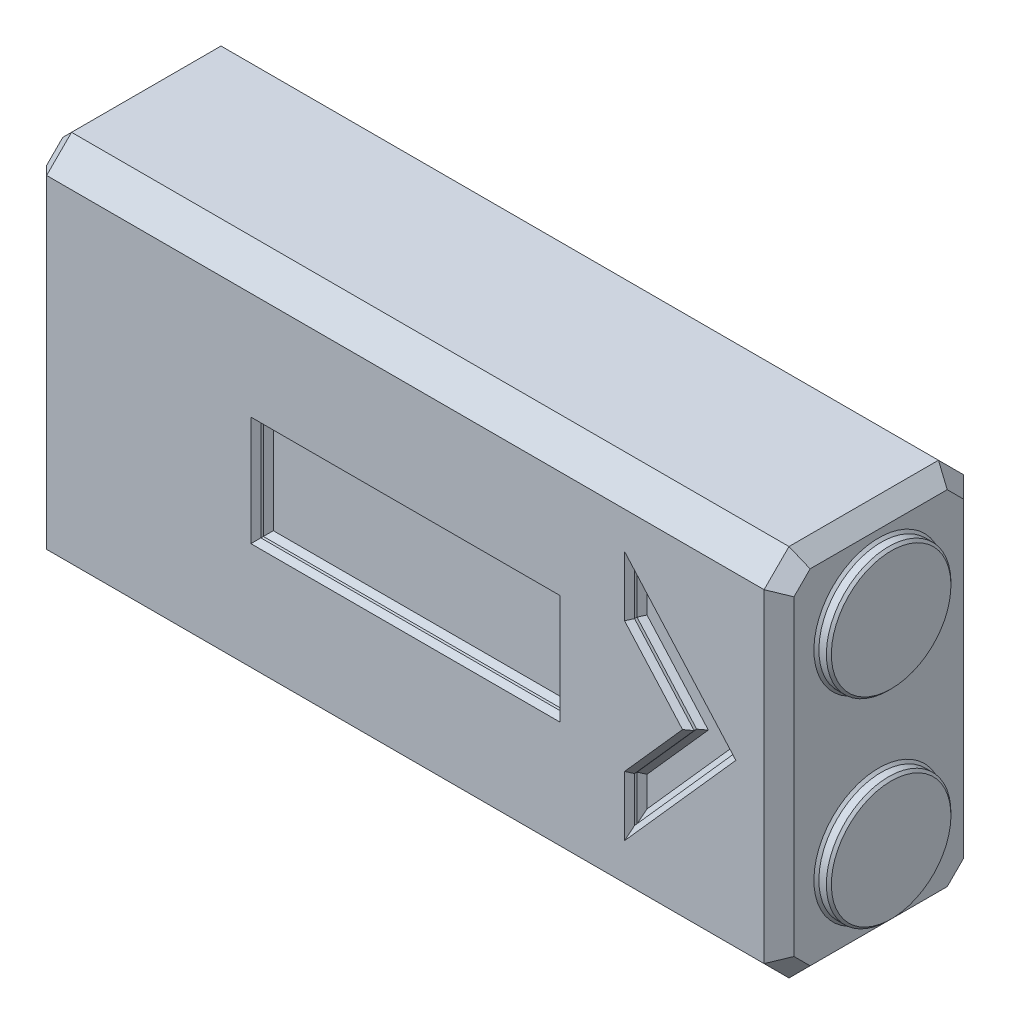
SolidWorks part; units mm, degrees
ref_plane "Front Plane" through (0, 0, 0) normal (0, 0, 1) x (1, 0, 0)
ref_plane "Top Plane" through (0, 0, 0) normal (0, 1, 0) x (1, 0, 0)
ref_plane "Right Plane" through (0, 0, 0) normal (1, 0, 0) x (0, 0, -1)
sketch "Sketch1" plane through (0, 0, 0) normal (0, 1, 0) x (1, 0, 0)
  line L0 (-75, 150) -> (75, -150) construction
  line L1 (-75, 150) -> (75, 150)
  line L2 (-75, 150) -> (-75, -150)
  line L3 (-75, -150) -> (75, -150)
  line L4 (75, 150) -> (75, -150)
  dimension "D1" = 150
  dimension "D2" = 300
extrude "Boss-Extrude1" add sketch "Sketch1" along normal mid plane 80
sketch "Sketch2" plane through (0, 0, 150) normal (0, 0, 1) x (1, 0, 0)
  line L0 (0, 51.0302) -> (0, -58.9796) construction
  line L1 (-40, 0) -> (40, 0) construction
  line L2 (-40, 35) -> (-100, 35) construction
  line L3 (-100, 35) -> (-100, -35) construction
  line L4 (-100, -35) -> (-40, -35) construction
  circle A0 centre (-40, 0) radius 25
  circle A1 centre (40, 0) radius 25
  arc A2 (-40, -35) -> (-40, 35) centre (-40, 0) ccw construction
  dimension "D1" = 50
  dimension "D2" = 70
  dimension "D3" = 80
  dimension "D4" = 60
extrude "Boss-Extrude2" add sketch "Sketch2" along normal blind 5
sketch "Sketch3" plane through (0, 40, 0) normal (0, 1, 0) x (1, 0, 0)
  line L0 (-20, 60) -> (20, -60) construction
  line L1 (-20, 60) -> (20, 60)
  line L2 (-20, 60) -> (-20, -60)
  line L3 (-20, -60) -> (20, -60)
  line L4 (20, 60) -> (20, -60)
  dimension "D1" = 40
  dimension "D2" = 120
extrude "Cut-Extrude1" cut sketch "Sketch3" against normal blind 5
sketch "Sketch4" plane through (0, 40, 0) normal (0, 1, 0) x (1, 0, 0)
  line L0 (0, -130) -> (-45, -90)
  line L1 (-45, -90) -> (-26.9376, -90)
  line L2 (-26.9376, -90) -> (0, -113.9445)
  line L3 (0, 0) -> (0, -130) construction
  line L4 (26.9376, -90) -> (0, -113.9445)
  line L5 (45, -90) -> (26.9376, -90)
  line L6 (0, -130) -> (45, -90)
  line L7 (-75, -150) -> (75, -150) construction
  dimension "D1" = 12
  dimension "D2" = 40
  dimension "D3" = 90
  dimension "D4" = 20
extrude "Cut-Extrude2" cut sketch "Sketch4" against normal blind 5
chamfer "Chamfer2" distance 10 angle 45 4 edges at (75, -40, 0) (-75, -40, 0) (75, 40, 0) (-75, 40, 0)
chamfer "Chamfer3" distance 2 angle 45 20 edges at (0, 35, -60) (20, 35, 0) (0, 35, 60) (-20, 35, 0) (0, 40, 60) (20, 40, 0) (-20, 40, 0) (0, 40, -60) (-22.5, 35, 110) (-35.9688, 35, 90) (-13.4688, 35, 101.9723) (13.4688, 35, 101.9723) (35.9688, 35, 90) (22.5, 35, 110) (-22.5, 40, 110) (-35.9688, 40, 90) (-13.4688, 40, 101.9723) (13.4688, 40, 101.9723) (35.9688, 40, 90) (22.5, 40, 110)
mirror "Mirror1" about plane through (0, 0, 0) normal (0, 0, 1) of "Boss-Extrude2"
chamfer "Chamfer4" distance 1 angle 45 4 edges at (15, 0, -155) (-15, 0, -155) (15, 0, 155) (-15, 0, 155)
chamfer "Chamfer5" distance 1 angle 45 4 edges at (-15, 0, -150) (15, 0, -150) (-65, 0, 150) (15, 0, 150)
chamfer "Chamfer6" distance 6 angle 45 16 edges at (0, -40, 150) (70, -35, 150) (75, 0, 150) (70, 35, 150) (0, 40, 150) (-70, 35, 150) (-75, 0, 150) (-70, -35, 150) (-70, -35, -150) (-75, 0, -150) (-70, 35, -150) (0, -40, -150) (70, -35, -150) (0, 40, -150) (70, 35, -150) (75, 0, -150)
move or copy body "Body-Move/Copy1" bodies to move or copy 104 copy no rotation origin (0, 0, 0) rotation axis (0.5774, 0.5774, 0.5774) rotation angle 120
